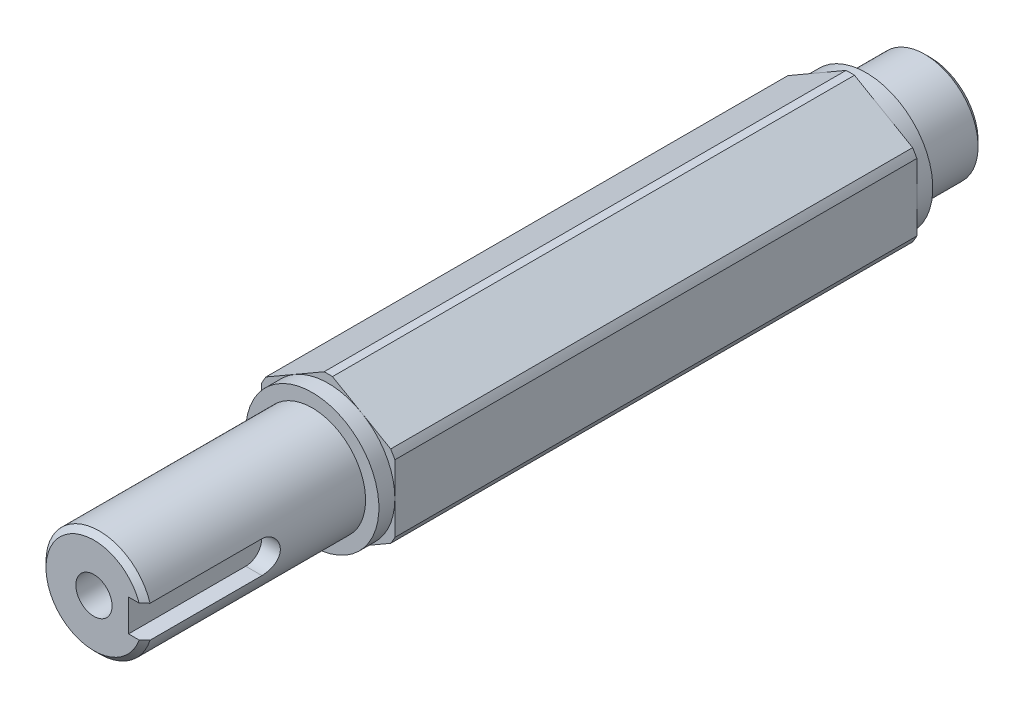
SolidWorks part; units mm, degrees
material "S45C"
ref_plane "Front Plane" through (0, 0, 0) normal (0, 0, 1) x (1, 0, 0)
ref_plane "Top Plane" through (0, 0, 0) normal (0, 1, 0) x (1, 0, 0)
ref_plane "Right Plane" through (0, 0, 0) normal (1, 0, 0) x (0, 0, -1)
sketch "Sketch1" plane through (0, 0, 0) normal (0, 0, 1) x (1, 0, 0)
  line L1 (0, 14.4338) -> (-12.5, 7.2169)
  line L2 (-12.5, 7.2169) -> (-12.5, -7.2169)
  line L3 (-12.5, -7.2169) -> (0, -14.4338)
  line L4 (0, -14.4338) -> (12.5, -7.2169)
  line L5 (12.5, -7.2169) -> (12.5, 7.2169)
  line L6 (12.5, 7.2169) -> (0, 14.4338)
  circle A0 centre (0, 0) radius 12.5 construction
  circle A1 centre (0, 0) radius 14
  dimension "D1" = 28
  dimension "D2" = 25
extrude "Boss-Extrude1" add sketch "Sketch1" along normal mid plane 98 contours L5 A1 L6 L1 L2 L3 L4
sketch "Sketch2" plane through (0, 0, 0) normal (1, 0, 0) x (0, 0, -1)
  line L0 (70.7525, 0) -> (-133.0929, 0) construction
  line L1 (-93, 0) -> (-93, 10)
  line L2 (-93, 10) -> (-52, 10)
  line L3 (-49, -6.3048) -> (-49, 6.3048) construction
  line L4 (-49, 12.5) -> (-49, 0)
  line L5 (-49, 0) -> (-93, 0)
  line L6 (52, 10) -> (64, 10)
  line L7 (49, -6.3048) -> (49, 6.3048) construction
  line L8 (64, 10) -> (64, 0)
  line L11 (64, 0) -> (49, 0)
  line L12 (49, 0) -> (49, 12.5)
  line L14 (-52, 10) -> (-52, 12.5)
  line L15 (-52, 12.5) -> (-49, 12.5)
  line L16 (-49, 7.6729) -> (-49, 13.9777) construction
  line L17 (52, 10) -> (52, 12.5)
  line L18 (52, 12.5) -> (49, 12.5)
  dimension "D1" = 20
  dimension "D2" = 25
  dimension "D3" = 104
  dimension "D4" = 12
  dimension "D7" = 41
revolve "Revolve1" add sketch "Sketch2" angle 360 about L0
chamfer "Chamfer1" distance 1 angle 45 2 edges at (-10, 0, 93) (-10, 0, -64)
hole_wizard "M8 Tapped Hole1" positions "3DSketch1" profile "Sketch3" tap size "M8" standard "ISO"
sketch3d "3DSketch1"
  circle A0 centre (0, 0, 93) radius 9 construction
  circle A1 centre (0, 0, -64) radius 9 construction
  point P0 (0, 0, 93)
  point P4 (0, 0, 102)
  point P5 (0, 0, -64)
  point P9 (0, 0, -73)
sketch "Sketch3" plane through (0, 0, 93) normal (1, 0, 0) x (0, -1, 0)
  line L0 (0, 0) -> (0, 21.7929)
  line L1 (0, 21.7929) -> (3.4, 19.75)
  line L2 (3.4, 19.75) -> (3.4, 0)
  line L5 (3.4, 0) -> (0, 0)
  line L10 (0, 21.7929) -> (-3.4, 19.75) construction
  line L11 (0, -6.35) -> (0, 107.95) construction
  dimension "Tap Drill Dia." = 6.8
  dimension "Tap Drill Depth" = 19.75
  dimension "Drill Angle" = 118
cosmetic thread "Hole Thread1" parameters "D1"=16, "D2"=8
cosmetic thread "Hole Thread2" parameters "D1"=16, "D2"=8
sketch "Sketch4" plane through (0, 0, 0) normal (1, 0, 0) x (0, 0, -1)
  line L0 (-93, 0) -> (-71, 0) construction
  line L3 (-93, -3) -> (-71, -3)
  line L4 (-93, 3) -> (-71, 3)
  line L5 (-93, 9) -> (-93, -9) construction
  arc A0 (-93, -3) -> (-93, 3) centre (-93, 0) cw
  arc A1 (-71, -3) -> (-71, 3) centre (-71, 0) ccw
  dimension "D2" = 22
  dimension "D3" = 3
  dimension "D4" = 3
extrude "Cut-Extrude1" cut sketch "Sketch4" against normal blind 3.5 from offset 10
